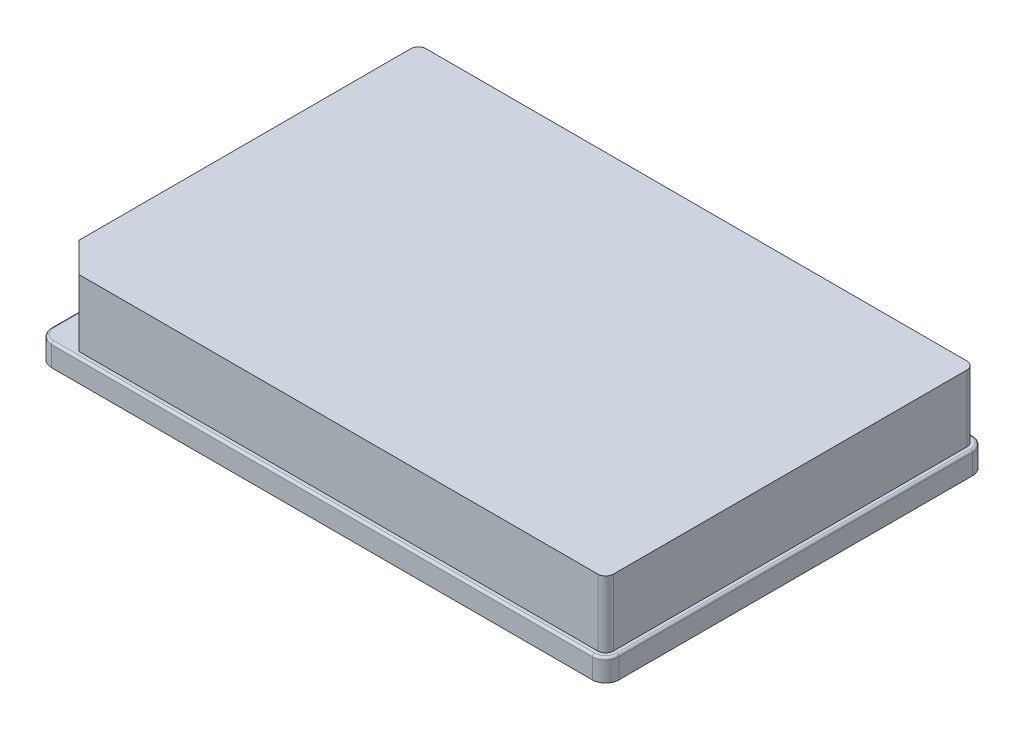
SolidWorks part; units mm, degrees
ref_plane "Front Plane" through (0, 0, 0) normal (0, 0, 1) x (1, 0, 0)
ref_plane "Top Plane" through (0, 0, 0) normal (0, 1, 0) x (1, 0, 0)
ref_plane "Right Plane" through (0, 0, 0) normal (1, 0, 0) x (0, 0, -1)
sketch "Sketch1" plane through (0, 0, 0) normal (0, 1, 0) x (1, 0, 0)
  line L0 (-63.875, -42.8) -> (63.875, 42.8) construction
  line L1 (-63.875, -42.8) -> (63.875, -42.8)
  line L2 (-63.875, -42.8) -> (-63.875, 42.8)
  line L3 (-63.875, 42.8) -> (63.875, 42.8)
  line L4 (63.875, -42.8) -> (63.875, 42.8)
  point P4 (0, 0)
  dimension "D1" = 85.6
  dimension "D2" = 127.75
extrude "Boss-Extrude1" add sketch "Sketch1" along normal blind 20
fillet "Fillet1" radius 3 4 edges at (-63.875, 10, -42.8) (-63.875, 10, 42.8) (63.875, 10, 42.8) (63.875, 10, -42.8)
sketch "Sketch3" plane through (0, 20, 0) normal (0, 1, 0) x (1, 0, 0)
  line L0 (-63.875, 39.8) -> (-63.875, -39.8) construction
  line L1 (60.875, 42.8) -> (-60.875, 42.8) construction
  line L2 (63.875, -39.8) -> (63.875, 39.8) construction
  line L3 (-60.875, -42.8) -> (60.875, -42.8) construction
  line L4 (-63.875, 39.8) -> (-63.875, -39.8)
  line L5 (60.875, 42.8) -> (-60.875, 42.8)
  line L6 (63.875, -39.8) -> (63.875, 39.8)
  line L7 (-60.875, -42.8) -> (60.875, -42.8)
  line L8 (-62.625, 39.8) -> (-62.625, -34.8)
  line L9 (-55.875, -41.55) -> (60.875, -41.55)
  line L10 (62.625, -39.8) -> (62.625, 39.8)
  line L11 (60.875, 41.55) -> (-60.875, 41.55)
  line L12 (-62.625, -39.8) -> (-60.875, -41.55) construction
  line L13 (-62.625, -34.8) -> (-55.875, -41.55)
  line L14 (-62.625, -34.8) -> (-62.625, -39.8) construction
  line L15 (-60.875, -41.55) -> (-55.875, -41.55) construction
  line L17 (-62.625, 39.8) -> (-62.625, -39.8) construction
  line L18 (-60.875, -41.55) -> (60.875, -41.55) construction
  arc A0 (-60.875, 42.8) -> (-63.875, 39.8) centre (-60.875, 39.8) ccw construction
  arc A1 (63.875, 39.8) -> (60.875, 42.8) centre (60.875, 39.8) ccw construction
  arc A2 (60.875, -42.8) -> (63.875, -39.8) centre (60.875, -39.8) ccw construction
  arc A3 (-63.875, -39.8) -> (-60.875, -42.8) centre (-60.875, -39.8) ccw construction
  arc A4 (-60.875, 42.8) -> (-63.875, 39.8) centre (-60.875, 39.8) ccw
  arc A5 (63.875, 39.8) -> (60.875, 42.8) centre (60.875, 39.8) ccw
  arc A6 (60.875, -42.8) -> (63.875, -39.8) centre (60.875, -39.8) ccw
  arc A7 (-63.875, -39.8) -> (-60.875, -42.8) centre (-60.875, -39.8) ccw
  arc A9 (60.875, -41.55) -> (62.625, -39.8) centre (60.875, -39.8) ccw
  arc A10 (62.625, 39.8) -> (60.875, 41.55) centre (60.875, 39.8) ccw
  arc A11 (-60.875, 41.55) -> (-62.625, 39.8) centre (-60.875, 39.8) ccw
  arc A12 (-62.625, -39.8) -> (-60.875, -41.55) centre (-60.875, -39.8) ccw construction
  dimension "D2" = 5
  dimension "D1" = 1.25
extrude "Cut-Extrude2" cut sketch "Sketch3" against normal offset from surface (15 mm away) 5 up to face at (0, 0, 0)
fillet "Fillet5" radius 0.5 8 edges at (-62.9963, 5, 41.9213) (-63.875, 5, 0) (-62.9963, 5, -41.9213) (0, 5, -42.8) (62.9963, 5, -41.9213) (63.875, 5, 0) (62.9963, 5, 41.9213) (0, 5, 42.8)
